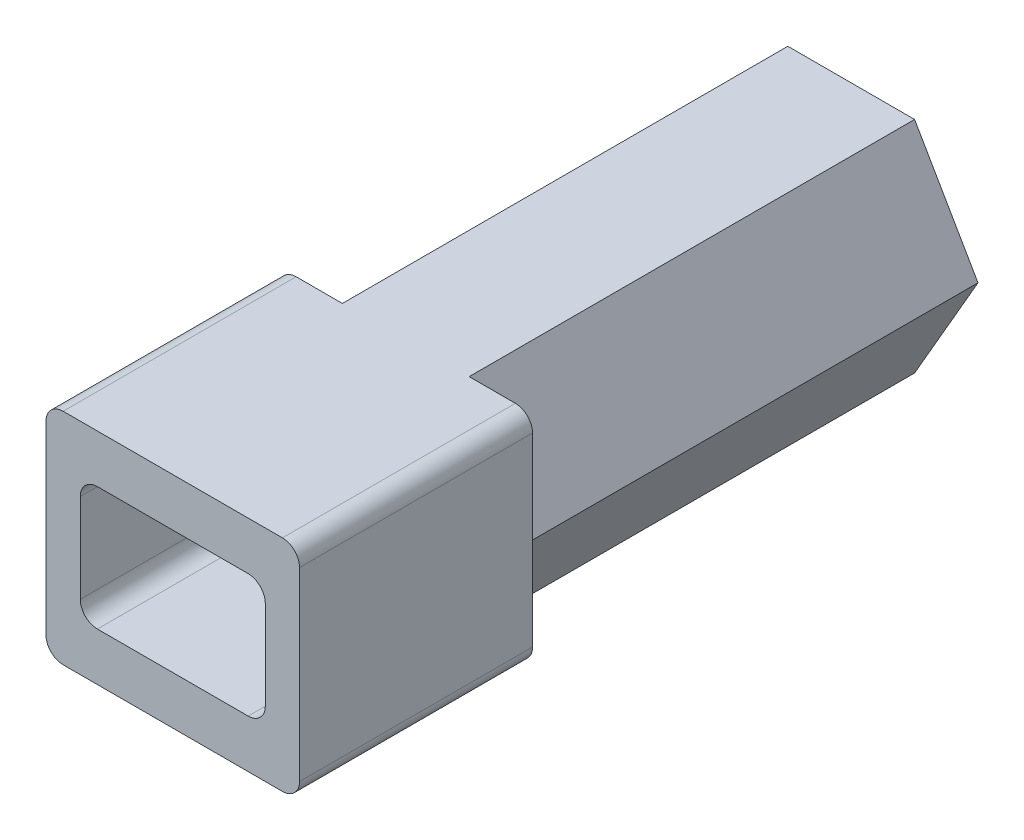
SolidWorks part; units mm, degrees
ref_plane "Ön Düzlem" through (0, 0, 0) normal (0, 0, 1) x (1, 0, 0)
ref_plane "Üst Düzlem" through (0, 0, 0) normal (0, 1, 0) x (1, 0, 0)
ref_plane "Sağ Düzlem" through (0, 0, 0) normal (1, 0, 0) x (0, 0, -1)
sketch "Çizim1" plane through (0, 0, 0) normal (0, 0, 1) x (1, 0, 0)
  line L1 (3.7, 0) -> (1.85, 3.2043)
  line L2 (1.85, 3.2043) -> (-1.85, 3.2043)
  line L3 (-1.85, 3.2043) -> (-3.7, 0)
  line L4 (-3.7, 0) -> (-1.85, -3.2043)
  line L5 (-1.85, -3.2043) -> (1.85, -3.2043)
  line L6 (1.85, -3.2043) -> (3.7, 0)
  circle A0 centre (0, 0) radius 3.2043 construction
  dimension "D1" = 7.4
extrude "Yükseklik-Ekstrüzyon1" add sketch "Çizim1" along normal blind 13
sketch "Çizim2" plane through (0, 0, 13) normal (0, 0, 1) x (1, 0, 0)
  line L1 (-2.2, -1.8) -> (2.2, -1.8)
  line L2 (-2.7, -1.3) -> (-2.7, 1.3)
  line L4 (2.7, -1.3) -> (2.7, 1.3)
  line L5 (-2.2, 1.8) -> (2.2, 1.8)
  line L6 (1.85, -3.2043) -> (3.2, -3.2043)
  line L8 (-3.7, -2) -> (-3.7, 2.3282)
  line L10 (3.7, -2) -> (3.7, 2.326)
  line L11 (3.7, -2.7043) -> (3.7, -2)
  line L12 (1.85, -3.2043) -> (-1.85, -3.2043)
  line L13 (-1.85, -3.2043) -> (-3.2, -3.2043)
  line L14 (-3.7, -2.7043) -> (-3.7, -2)
  line L15 (3.7, 2.326) -> (3.7, 2.7043)
  line L16 (1.85, 3.2043) -> (3.2, 3.2043)
  line L17 (-1.85, 3.2043) -> (-3.2, 3.2043)
  line L18 (-3.7, 2.7043) -> (-3.7, 2.3282)
  line L19 (1.85, 3.2043) -> (-1.85, 3.2043)
  arc A1 (2.2, -1.8) -> (2.7, -1.3) centre (2.2, -1.3) ccw
  arc A2 (-2.2, -1.8) -> (-2.7, -1.3) centre (-2.2, -1.3) cw
  arc A3 (-2.7, 1.3) -> (-2.2, 1.8) centre (-2.2, 1.3) cw
  arc A8 (2.2, 1.8) -> (2.7, 1.3) centre (2.2, 1.3) cw
  arc A9 (-3.2, -3.2043) -> (-3.7, -2.7043) centre (-3.2, -2.7043) cw
  arc A10 (3.2, -3.2043) -> (3.7, -2.7043) centre (3.2, -2.7043) ccw
  arc A11 (3.7, 2.7043) -> (3.2, 3.2043) centre (3.2, 2.7043) ccw
  arc A12 (-3.2, 3.2043) -> (-3.7, 2.7043) centre (-3.2, 2.7043) ccw
  point P0 (0, 0)
  point P18 (0, 0)
extrude "Yükseklik-Ekstrüzyon2" add sketch "Çizim2" along normal blind 6.8
sketch "Çizim3" plane through (0, 0, 0) normal (0, 0, -1) x (-1, 0, 0)
  circle A0 centre (0, 0) radius 1.25
extrude "Kes-Ekstrüzyon1" cut sketch "Çizim3" against normal blind 13.8
